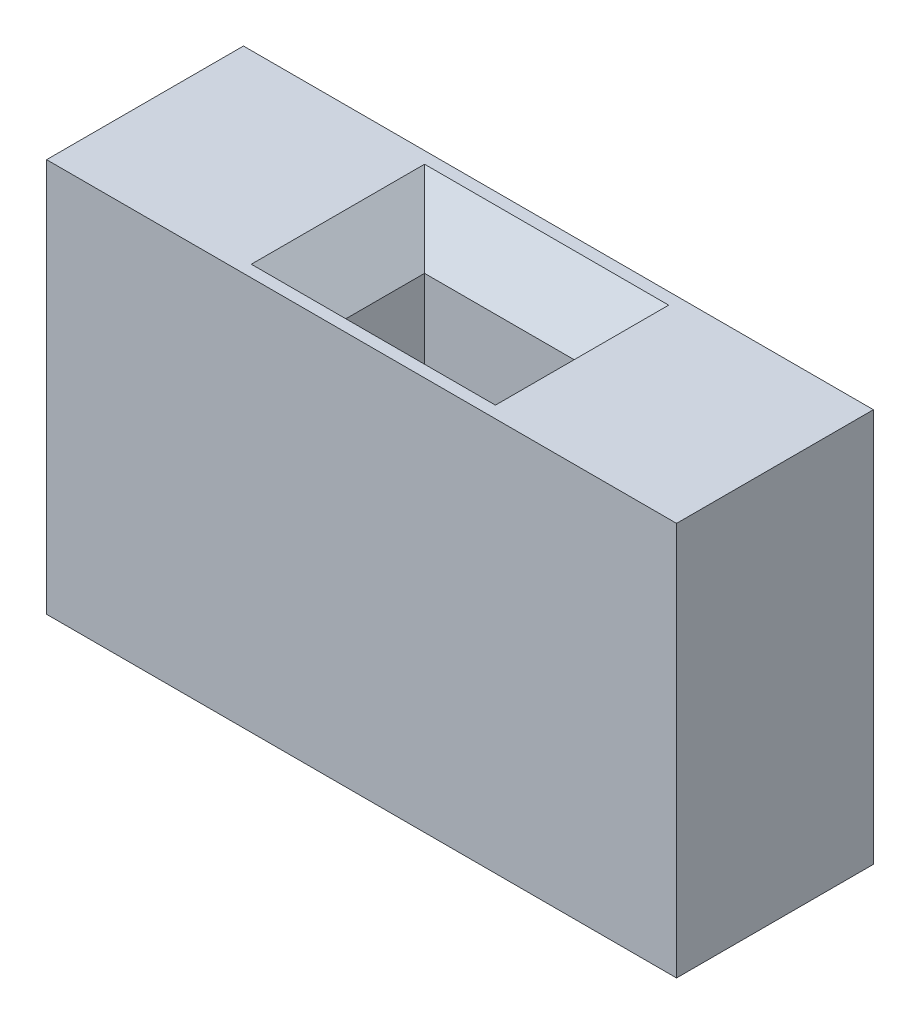
SolidWorks part; units mm, degrees
ref_plane "Front Plane" through (0, 0, 0) normal (0, 0, 1) x (1, 0, 0)
ref_plane "Top Plane" through (0, 0, 0) normal (0, 1, 0) x (1, 0, 0)
ref_plane "Right Plane" through (0, 0, 0) normal (1, 0, 0) x (0, 0, -1)
sketch "Sketch1" plane through (0, 0, 0) normal (0, 1, 0) x (1, 0, 0)
  line L1 (-0.04, -0.0125) -> (0.04, -0.0125)
  line L2 (-0.04, -0.0125) -> (-0.04, 0.0125)
  line L3 (-0.04, 0.0125) -> (0.04, 0.0125)
  line L4 (0.04, -0.0125) -> (0.04, 0.0125)
  line L5 (-0.04, -0.0125) -> (0.04, 0.0125) construction
  line L6 (-0.04, 0.0125) -> (0.04, -0.0125) construction
  point P0 (0, 0)
  dimension "D1" = 0.025
  dimension "D2" = 0.08
extrude "Boss-Extrude1" add sketch "Sketch1" along normal mid plane 0.05 contours L2 L3 L4 L1
sketch "Sketch2" plane through (0, 0.025, 0) normal (0, 1, 0) x (1, 0, 0)
  line L1 (-0.0095, -0.005) -> (0.0095, -0.005)
  line L2 (-0.0095, -0.005) -> (-0.0095, 0.005)
  line L3 (-0.0095, 0.005) -> (0.0095, 0.005)
  line L4 (0.0095, -0.005) -> (0.0095, 0.005)
  line L5 (-0.0095, -0.005) -> (0.0095, 0.005) construction
  line L6 (-0.0095, 0.005) -> (0.0095, -0.005) construction
  point P0 (0, 0)
  dimension "D1" = 0.01
  dimension "D2" = 0.019
extrude "Cut-Extrude1" cut sketch "Sketch2" against normal blind 0.04
chamfer "Chamfer1" distance 0.006 angle 45 4 edges at (0.0095, 0.025, 0) (0, 0.025, 0.005) (-0.0095, 0.025, 0) (0, 0.025, -0.005)
